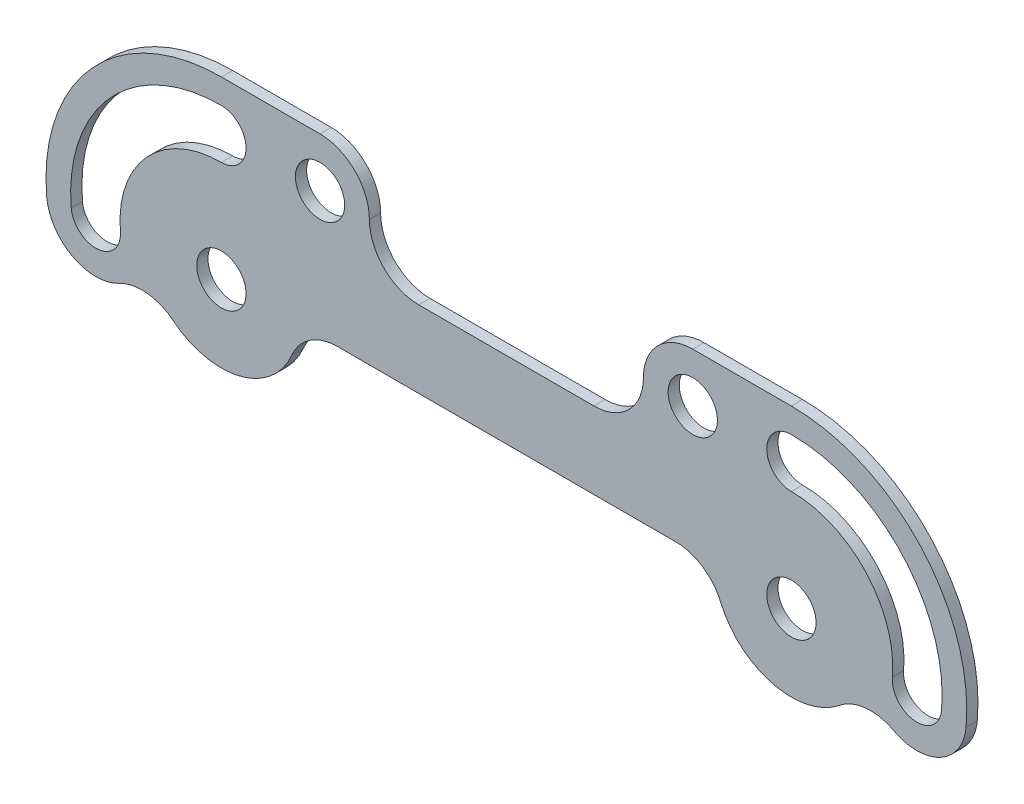
SolidWorks part; units mm, degrees
ref_plane "Front Plane" through (0, 0, 0) normal (0, 0, 1) x (1, 0, 0)
ref_plane "Top Plane" through (0, 0, 0) normal (0, 1, 0) x (1, 0, 0)
ref_plane "Right Plane" through (0, 0, 0) normal (1, 0, 0) x (0, 0, -1)
sketch "Sketch1" plane through (0, 0, 0) normal (0, 0, 1) x (1, 0, 0)
  line L0 (5.5562, 0) -> (35.7188, 0)
  line L1 (0, 5.5562) -> (41.275, 5.5562)
  line L2 (0, 5.5562) -> (0, -5.5562) construction
  line L3 (0, -5.5562) -> (41.275, -5.5562) construction
  line L4 (41.275, 5.5562) -> (41.275, -5.5562) construction
  line L5 (0, 5.5562) -> (41.275, 5.5562) construction
  line L6 (0, 5.5562) -> (0, -10.3188) construction
  line L7 (0, -10.3188) -> (41.275, -10.3188) construction
  line L8 (41.275, 5.5562) -> (41.275, -10.3188) construction
  line L9 (41.275, 0) -> (50.3684, -0.7956) construction
  line L10 (41.275, 9.1281) -> (41.275, 0) construction
  line L11 (0, 0) -> (-9.0934, -0.7956) construction
  line L12 (34.1312, 12.7) -> (41.275, 12.7)
  line L13 (0, 12.7) -> (7.1437, 12.7)
  circle A0 centre (0, 0) radius 5.5562 construction
  circle A1 centre (41.275, 0) radius 5.5562 construction
  arc A2 (0, 5.5562) -> (0, -5.5562) centre (0, 0) ccw
  arc A3 (41.275, -5.5562) -> (41.275, 5.5562) centre (41.275, 0) ccw
  circle A4 centre (0, 0) radius 1.7859
  circle A5 centre (41.275, 0) radius 1.7859
  arc A6 (0, -5.5562) -> (5.5562, 0) centre (0, 0) ccw
  arc A7 (35.7188, 0) -> (41.275, -5.5562) centre (41.275, 0) ccw
  circle A10 centre (0, 9.1281) radius 3.5719
  circle A12 centre (41.275, 9.1281) radius 1.7859
  circle A13 centre (50.3684, -0.7956) radius 3.5719
  circle A14 centre (50.3684, -0.7956) radius 1.7859
  circle A15 centre (0, 9.1281) radius 1.7859
  arc A16 (41.275, 9.1281) -> (50.3684, -0.7956) centre (41.275, 0) cw
  circle A17 centre (41.275, 9.1281) radius 3.5719
  circle A19 centre (34.1312, 9.1281) radius 3.5719
  arc A20 (41.275, 12.7) -> (53.9267, -1.1069) centre (41.275, 0) cw
  arc A21 (41.275, 10.9141) -> (52.1475, -0.9512) centre (41.275, 0) cw
  arc A22 (41.275, 7.3422) -> (48.5892, -0.6399) centre (41.275, 0) cw
  circle A23 centre (41.275, 0) radius 9.1281 construction
  circle A24 centre (47.0107, -7.101) radius 3.5719
  circle A25 centre (0, 0) radius 9.1281 construction
  circle A29 centre (-9.0934, -0.7956) radius 3.5719
  circle A30 centre (-5.7357, -7.101) radius 3.5719
  circle A31 centre (-9.0934, -0.7956) radius 1.7859
  circle A35 centre (26.9875, 9.1281) radius 3.5719
  circle A36 centre (34.1312, 9.1281) radius 1.7859
  circle A37 centre (7.1437, 9.1281) radius 3.5719
  circle A38 centre (14.2875, 9.1281) radius 3.5719
  circle A39 centre (7.1437, 9.1281) radius 1.7859
  arc A40 (-7.3142, -0.6399) -> (0, 7.3422) centre (0, 0) cw
  arc A41 (-10.8725, -0.9512) -> (0, 10.9141) centre (0, 0) cw
  arc A42 (-12.6517, -1.1069) -> (0, 12.7) centre (0, 0) cw
  circle A44 centre (32.8747, -3.5719) radius 3.5719
  circle A45 centre (8.4003, -3.5719) radius 3.5719
  dimension "D1" = 41.275
  dimension "D2" = 11.1125
  dimension "D3" = 3.5719
  dimension "D5" = 95
  dimension "D6" = 7.1437
  dimension "D7" = 3.5719
  dimension "D8" = 95
  dimension "D4" = 15.875
extrude "Boss-Extrude1" add sketch "Sketch1" along normal blind 0.8128 contours L0 A7 A3 L1 A2 A6 A4 A5 | A38 A37 L1 | A37 A39 | A37 L13 A10 | A37 A10 L1 | A10 A41 A15 A40 | A40 A29 A2 A10 | A42 A29 A41 A10 | A31 A41 A29 A40 | A30 A2 A29 | A35 L1 A19 | A19 A36 | A19 A17 L12 | A19 L1 A17 | A22 A12 A21 A17 | A22 A17 A3 A13 | A17 A21 A13 A20 | A22 A13 A21 A14 | A24 A13 A3 | A45 L0 A6 | A44 A7 L0
